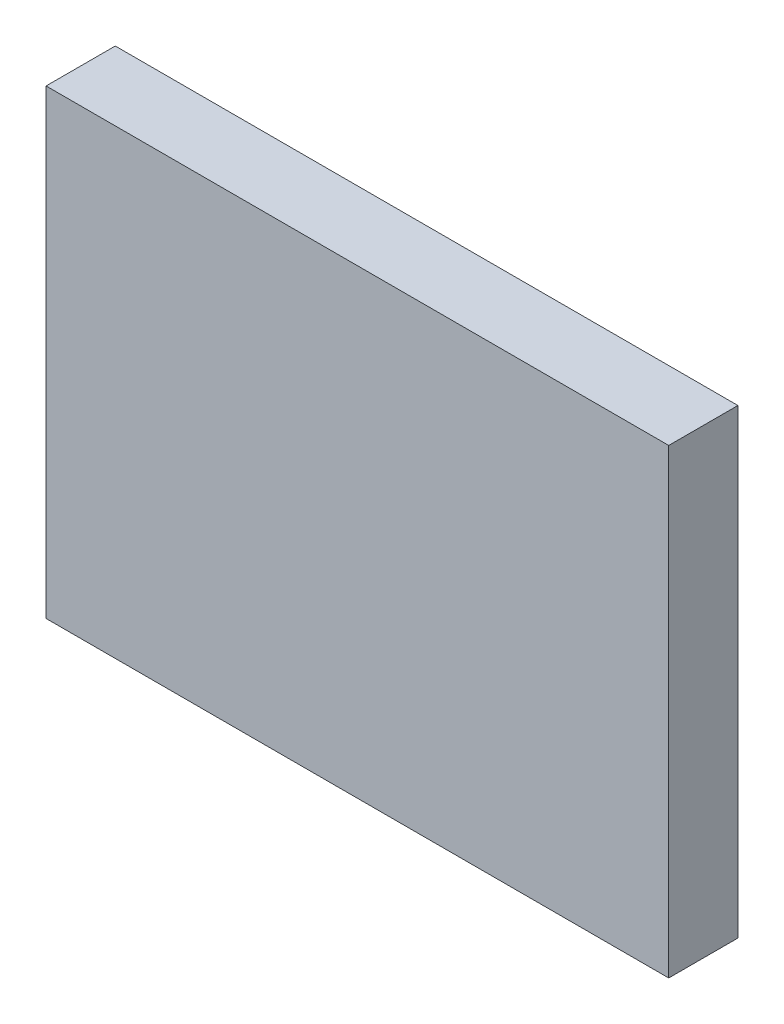
SolidWorks part; units mm, degrees
ref_plane "Front Plane" through (0, 0, 0) normal (0, 0, 1) x (1, 0, 0)
ref_plane "Top Plane" through (0, 0, 0) normal (0, 1, 0) x (1, 0, 0)
ref_plane "Right Plane" through (0, 0, 0) normal (1, 0, 0) x (0, 0, -1)
sketch "Sketch1" plane through (0, 0, 0) normal (0, 0, 1) x (1, 0, 0)
  line L1 (-10.8976, 5.3145) -> (16.1024, 5.3145)
  line L2 (-10.8976, 5.3145) -> (-10.8976, -14.6855)
  line L3 (-10.8976, -14.6855) -> (16.1024, -14.6855)
  line L4 (16.1024, 5.3145) -> (16.1024, -14.6855)
  dimension "D1" = 27
  dimension "D2" = 20
extrude "Boss-Extrude1" add sketch "Sketch1" along normal blind 3
